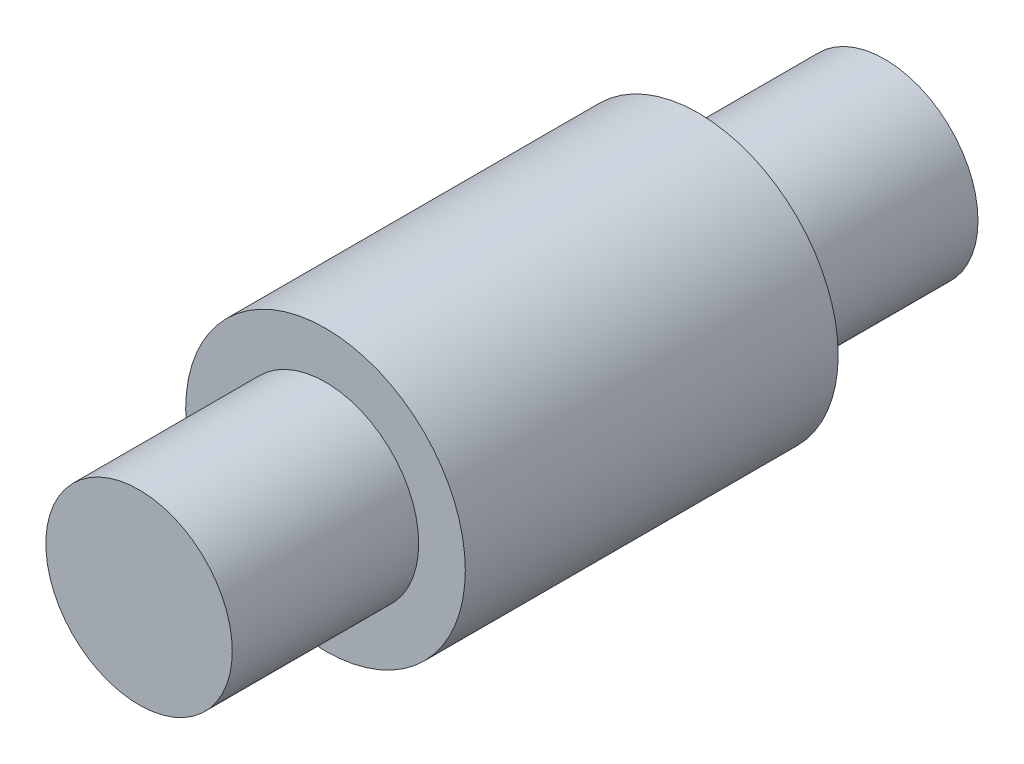
SolidWorks part; units mm, degrees
ref_plane "Front Plane" through (0, 0, 0) normal (0, 0, 1) x (1, 0, 0)
ref_plane "Top Plane" through (0, 0, 0) normal (0, 1, 0) x (1, 0, 0)
ref_plane "Right Plane" through (0, 0, 0) normal (1, 0, 0) x (0, 0, -1)
sketch "Sketch1" plane through (0, 0, 0) normal (0, 1, 0) x (1, 0, 0)
  line L0 (0, 0) -> (3.175, 0)
  line L1 (3.175, 0) -> (3.175, -6.35)
  line L2 (3.175, -6.35) -> (4.7625, -6.35)
  line L3 (4.7625, -6.35) -> (4.7625, -19.05)
  line L4 (4.7625, -19.05) -> (3.175, -19.05)
  line L5 (3.175, -19.05) -> (3.175, -25.4)
  line L6 (3.175, -25.4) -> (0, -25.4)
  line L7 (0, -25.4) -> (0, 0)
  dimension "D1" = 4.7625
  dimension "D2" = 3.175
  dimension "D3" = 25.4
  dimension "D4" = 12.7
revolve "Revolve1" add sketch "Sketch1" angle 360 about L7
